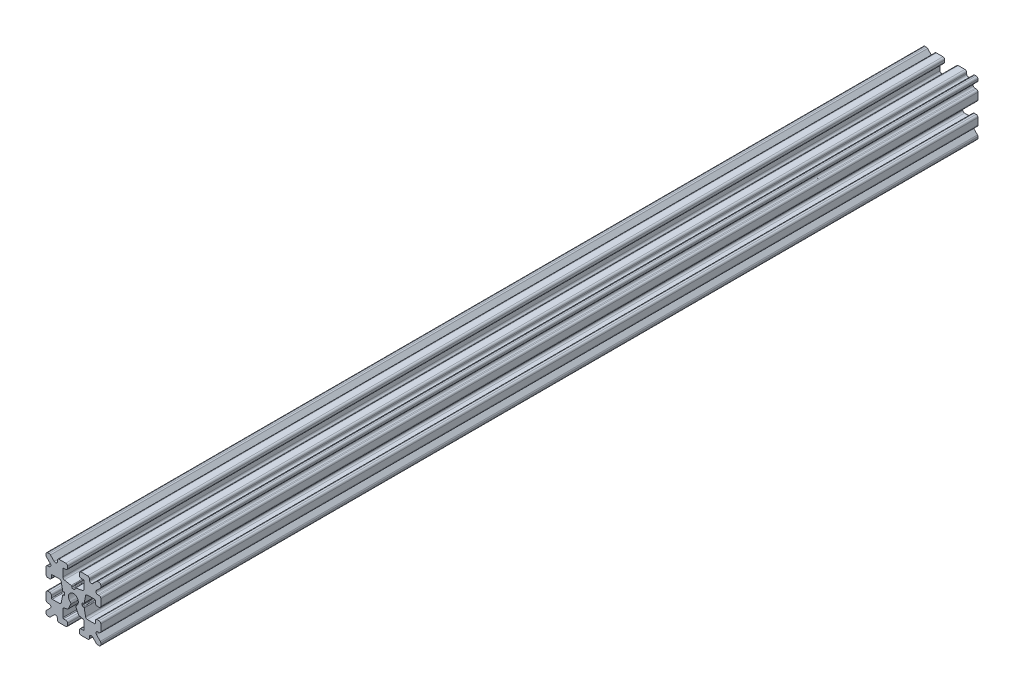
SolidWorks part; units mm, degrees
ref_plane "Front Plane" through (0, 0, 0) normal (0, 0, 1) x (1, 0, 0)
ref_plane "Top Plane" through (0, 0, 0) normal (0, 1, 0) x (1, 0, 0)
ref_plane "Right Plane" through (0, 0, 0) normal (1, 0, 0) x (0, 0, -1)
sketch "Sketch1" plane through (0, 0, 0) normal (0, 0, 1) x (1, 0, 0)
  line L1 (-7.5, -7.5) -> (7.5, -7.5)
  line L2 (-7.5, -7.5) -> (-7.5, 7.5)
  line L3 (-7.5, 7.5) -> (7.5, 7.5)
  line L4 (7.5, -7.5) -> (7.5, 7.5)
  line L5 (-7.5, -7.5) -> (7.5, 7.5) construction
  line L6 (-7.5, 7.5) -> (7.5, -7.5) construction
  circle A0 centre (0, 0) radius 1.35
  point P0 (0, 0)
  dimension "D2" = 2.7
  dimension "D1" = 15
extrude "Boss-Extrude1" add sketch "Sketch1" along normal mid plane 240
fillet "Fillet1" radius 0.5 4 edges at (7.5, -7.5, 0) (-7.5, -7.5, 0) (7.5, 7.5, 0) (-7.5, 7.5, 0)
sketch "Sketch2" plane through (0, 0, 120) normal (0, 0, 1) x (1, 0, 0)
  line L0 (-7.5, 7) -> (-7.5, -7) construction
  line L1 (-7.5, 1.6) -> (-6, 1.6)
  line L2 (-7.5, 1.6) -> (-7.5, -1.6)
  line L3 (-7.5, -1.6) -> (-6, -1.6)
  line L4 (-6, 1.6) -> (-6, 2.9)
  line L5 (0, 0) -> (-12.1036, 0) construction
  line L6 (-6, -2.9) -> (-3.4, -2.9)
  line L7 (0, 0) -> (-7, 7) construction
  line L8 (-6, 2.9) -> (-3.4, 2.9)
  line L9 (-3.4, -2.9) -> (-3.4, 2.9)
  line L10 (55, 0) -> (-55, 0) construction
  line L11 (-6, -2.9) -> (-6, -1.6)
  line L12 (2.9, 6) -> (1.6, 6)
  line L13 (2.9, 3.4) -> (-2.9, 3.4)
  line L14 (-2.9, 6) -> (-2.9, 3.4)
  line L15 (2.9, 6) -> (2.9, 3.4)
  line L16 (-1.6, 6) -> (-2.9, 6)
  line L17 (1.6, 7.5) -> (1.6, 6)
  line L18 (-1.6, 7.5) -> (1.6, 7.5)
  line L19 (-1.6, 7.5) -> (-1.6, 6)
  line L20 (-1.6, -7.5) -> (-1.6, -6)
  line L21 (-1.6, -7.5) -> (1.6, -7.5)
  line L22 (1.6, -7.5) -> (1.6, -6)
  line L23 (-1.6, -6) -> (-2.9, -6)
  line L24 (2.9, -6) -> (2.9, -3.4)
  line L25 (-2.9, -6) -> (-2.9, -3.4)
  line L26 (2.9, -3.4) -> (-2.9, -3.4)
  line L27 (2.9, -6) -> (1.6, -6)
  line L28 (6, -2.9) -> (6, -1.6)
  line L29 (3.4, -2.9) -> (3.4, 2.9)
  line L30 (6, 2.9) -> (3.4, 2.9)
  line L31 (6, -2.9) -> (3.4, -2.9)
  line L32 (6, 1.6) -> (6, 2.9)
  line L33 (7.5, -1.6) -> (6, -1.6)
  line L34 (7.5, 1.6) -> (7.5, -1.6)
  line L35 (7.5, 1.6) -> (6, 1.6)
  dimension "D1" = 3.2
  dimension "D2" = 5.8
  dimension "D3" = 1.5
  dimension "D4" = 2.6
extrude "Cut-Extrude1" cut sketch "Sketch2" against normal through all
sketch "Sketch4" plane through (0, 0, 120) normal (0, 0, 1) x (1, 0, 0)
  line L0 (-3.4, 2.9) -> (-2.85, 0)
  line L1 (55, 0) -> (-55, 0) construction
  line L2 (-2.85, 0) -> (-3.4, -2.9)
  line L3 (-3.4, -2.9) -> (-3.4, 2.9) construction
  line L4 (-3.4, 2.9) -> (-3.4, -2.9)
  line L5 (-2.9, 3.4) -> (0, 2.85)
  line L6 (0, 2.85) -> (2.9, 3.4)
  line L7 (2.9, 3.4) -> (-2.9, 3.4)
  line L8 (3.4, 2.9) -> (2.85, 0)
  line L9 (2.85, 0) -> (3.4, -2.9)
  line L10 (3.4, -2.9) -> (3.4, 2.9)
  line L11 (-2.9, -3.4) -> (0, -2.85)
  line L12 (0, -2.85) -> (2.9, -3.4)
  line L13 (2.9, -3.4) -> (-2.9, -3.4)
  circle A2 centre (0, 0) radius 2.85
  circle A3 centre (0, 0) radius 2.85 construction
  dimension "D1" = 1.5
extrude "Cut-Extrude3" cut sketch "Sketch4" against normal through all
fillet "Fillet3" radius 0.5 16 edges at (-6, -1.6, 0) (-7.5, -1.6, 0) (-6, 1.6, 0) (-7.5, 1.6, 0) (-1.6, -7.5, 0) (-1.6, -6, 0) (1.6, -7.5, 0) (1.6, -6, 0) (6, -1.6, 0) (7.5, -1.6, 0) (7.5, 1.6, 0) (6, 1.6, 0) (1.6, 7.5, 0) (1.6, 6, 0) (-1.6, 7.5, 0) (-1.6, 6, 0)
fillet "Fillet4" radius 0.5 8 edges at (-3.4, 2.9, 0) (-3.4, -2.9, 0) (2.9, -3.4, 0) (-2.9, -3.4, 0) (3.4, -2.9, 0) (3.4, 2.9, 0) (-2.9, 3.4, 0) (2.9, 3.4, 0)
fillet "Fillet5" radius 3 4 edges at (0, -2.85, 0) (2.85, 0, 0) (-2.85, 0, 0) (0, 2.85, 0)
fillet "Fillet6" radius 0.2 8 edges at (-2.9, -6, 0) (2.9, -6, 0) (6, -2.9, 0) (6, 2.9, 0) (2.9, 6, 0) (-2.9, 6, 0) (-6, -2.9, 0) (-6, 2.9, 0)
sketch "Sketch5" plane through (0, 0, 120) normal (0, 0, 1) x (1, 0, 0)
  line L0 (0, 0) -> (-7, 7) construction
  line L1 (-7.5, 6.4393) -> (-5.4607, 4.4)
  line L2 (-6.4393, 7.5) -> (-4.4, 5.4607)
  line L3 (-7.5, 4.4) -> (-5.4607, 4.4)
  line L4 (-3.8141, 2.9) -> (-5.8, 2.9) construction
  line L5 (0, 0) -> (-12.1819, 0) construction
  line L6 (-4.4, 7.5) -> (-4.4, 5.4607)
  line L7 (-2.9, 5.8) -> (-2.9, 3.8141) construction
  line L8 (-7.5, 6.4393) -> (-7.5, 4.4)
  line L9 (-7.5, 7) -> (-7.5, 2.1) construction
  line L10 (2.1, -7.5) -> (7, -7.5) construction
  line L11 (7.5, -7) -> (7.5, -2.1) construction
  line L12 (7, 7.5) -> (2.1, 7.5) construction
  line L13 (-2.1, 7.5) -> (-7, 7.5) construction
  line L14 (-4.4, 7.5) -> (-6.4393, 7.5)
  line L16 (55, 0) -> (-55, 0) construction
  line L17 (0, 0) -> (0, 10.993) construction
  line L18 (0, -54.6431) -> (0, 54.6431) construction
  line L20 (4.4, 7.5) -> (6.4393, 7.5)
  line L22 (7.5, 6.4393) -> (7.5, 4.4)
  line L23 (4.4, 7.5) -> (4.4, 5.4607)
  line L24 (7.5, 4.4) -> (5.4607, 4.4)
  line L25 (6.4393, 7.5) -> (4.4, 5.4607)
  line L26 (7.5, 6.4393) -> (5.4607, 4.4)
  line L27 (7.5, -6.4393) -> (5.4607, -4.4)
  line L28 (6.4393, -7.5) -> (4.4, -5.4607)
  line L29 (7.5, -4.4) -> (5.4607, -4.4)
  line L30 (4.4, -7.5) -> (4.4, -5.4607)
  line L31 (7.5, -6.4393) -> (7.5, -4.4)
  line L33 (4.4, -7.5) -> (6.4393, -7.5)
  line L36 (-4.4, -7.5) -> (-6.4393, -7.5)
  line L38 (-7.5, -6.4393) -> (-7.5, -4.4)
  line L39 (-4.4, -7.5) -> (-4.4, -5.4607)
  line L40 (-7.5, -4.4) -> (-5.4607, -4.4)
  line L41 (-6.4393, -7.5) -> (-4.4, -5.4607)
  line L42 (-7.5, -6.4393) -> (-5.4607, -4.4)
  dimension "D1" = 1.5
  dimension "D2" = 1.5
  dimension "D3" = 1.5
extrude "Cut-Extrude4" cut sketch "Sketch5" against normal through all
fillet "Fillet8" radius 0.5 24 edges at (-5.4607, 4.4, 0) (-7.5, 4.4, 0) (-5.4607, -4.4, 0) (-7.5, -4.4, 0) (-4.4, -7.5, 0) (-4.4, -5.4607, 0) (4.4, -7.5, 0) (4.4, -5.4607, 0) (5.4607, -4.4, 0) (7.5, -4.4, 0) (7.5, 4.4, 0) (5.4607, 4.4, 0) (4.4, 5.4607, 0) (4.4, 7.5, 0) (-4.4, 5.4607, 0) (-4.4, 7.5, 0) (-6.4393, 7.5, 0) (-7.5, 6.4393, 0) (6.4393, 7.5, 0) (7.5, 6.4393, 0) (6.4393, -7.5, 0) (7.5, -6.4393, 0) (-6.4393, -7.5, 0) (-7.5, -6.4393, 0)
sketch "Sketch6" plane through (0, 0, 120) normal (0, 0, 1) x (1, 0, 0)
  line L0 (0, 0) -> (0, 11.013) construction
  line L1 (0.559, 2.956) -> (2.1235, 2.956) construction
  line L2 (0, -54.6431) -> (0, 54.6431) construction
  line L3 (0, 0) -> (7, 7) construction
  line L4 (8.6552, 0.4445) -> (8.6552, -0.4445)
  line L5 (2.406, 0.4445) -> (8.6552, 0.4445)
  line L8 (2.406, -0.4445) -> (2.406, 0.4445)
  line L10 (8.6552, -0.4445) -> (2.406, -0.4445)
  line L11 (-8.6552, -0.4445) -> (-2.406, -0.4445)
  line L12 (-2.406, -0.4445) -> (-2.406, 0.4445)
  line L14 (-0.4445, 8.6552) -> (-0.4445, 2.406)
  line L15 (-0.4445, 2.406) -> (0.4445, 2.406)
  line L17 (0.4445, 2.406) -> (0.4445, 8.6552)
  line L18 (0.4445, 8.6552) -> (-0.4445, 8.6552)
  line L20 (-2.406, 0.4445) -> (-8.6552, 0.4445)
  line L21 (-8.6552, 0.4445) -> (-8.6552, -0.4445)
  point P7 (0, 2.5973)
  dimension "D3" = 0.55
  dimension "D1" = 0.889
extrude "Cut-Extrude5" cut sketch "Sketch6" against normal through all
sketch "Sketch7" plane through (0, 0, 120) normal (0, 0, 1) x (1, 0, 0)
  line L0 (0, 0) -> (-2.1533, -4.6178)
  line L1 (-2.1533, -4.6178) -> (2.1533, -4.6178)
  line L2 (2.1533, -4.6178) -> (0, 0)
  line L3 (0, 0) -> (0, -8.6832) construction
  line L4 (0, -54.6431) -> (0, 54.6431) construction
  dimension "D1" = 50
extrude "Cut-Extrude6" cut sketch "Sketch7" against normal through all
fillet "Fillet9" radius 0.5 4 edges at (0.5705, -1.2235, 0) (-0.5705, -1.2235, 0) (1.4579, -3.1265, 0) (-1.4579, -3.1265, 0)
fillet "Fillet10" radius 0.2 12 edges at (-2.406, 0.4445, 0) (-2.406, -0.4445, 0) (0.4445, 2.406, 0) (-0.4445, 2.406, 0) (2.406, 0.4445, 0) (2.406, -0.4445, 0) (-2.9366, -0.4445, 0) (-2.9366, 0.4445, 0) (2.9366, -0.4445, 0) (2.9366, 0.4445, 0) (0.4445, 2.9366, 0) (-0.4445, 2.9366, 0)
sketch "Sketch10" plane through (0, 0, 120) normal (0, 0, 1) x (1, 0, 0)
  line L0 (2.7, 6) -> (2.1, 6) construction
  line L1 (-2.75, 6) -> (2.75, 6)
  line L2 (-2.75, 6) -> (-2.75, 3.6)
  line L3 (-2.75, 3.6) -> (2.75, 3.6)
  line L4 (2.75, 6) -> (2.75, 3.6)
  line L5 (0, 0) -> (0, 8.8277) construction
  line L6 (-3.2398, 3.994) -> (-2.2083, 2.8606) construction
  line L7 (-3.878, 3.2131) -> (-3.2018, 2.4701) construction
  line L8 (-2.406, -0.2445) -> (-2.406, 0.2445) construction
  line L9 (-2.1, 7.5) -> (-3.9, 7.5) construction
  line L10 (-1.5, 7.5) -> (1.5, 7.5)
  line L11 (-1.5, 7.5) -> (-1.5, 3.5)
  line L12 (-1.5, 3.5) -> (1.5, 3.5)
  line L13 (1.5, 7.5) -> (1.5, 3.5)
  arc A1 (-3.3228, 2.4932) -> (-3.8141, 2.9) centre (-3.8141, 2.4) ccw construction
  arc A2 (-2.9, 3.8141) -> (-2.4932, 3.3228) centre (-2.4, 3.8141) ccw construction
  arc A3 (0.88, -1.0238) -> (-0.88, -1.0238) centre (0, 0) ccw construction
  point P19 (-1.35, 0)
  point P20 (-2.406, 0)
  dimension "D1" = 2.4
  dimension "D2" = 5.5
  dimension "D3" = 0.9976
  dimension "D4" = 3
  dimension "D5" = 4
sketch "Sketch11" plane through (0, 0, 120) normal (0, 0, 1) x (1, 0, 0)
  line L0 (-7.5, 7) -> (-7.5, 6.6464) construction
  line L1 (-7.5, 7.5) -> (7.5, 7.5) construction
  line L2 (-7.5, 7.5) -> (-7.5, -7.5) construction
  line L3 (-7.5, -7.5) -> (7.5, -7.5) construction
  line L4 (7.5, 7.5) -> (7.5, -7.5) construction
  line L5 (-7, -7.5) -> (-6.6464, -7.5) construction
  line L6 (7.5, 6.6464) -> (7.5, 7) construction
  line L7 (-2.1, 7.5) -> (-3.9, 7.5) construction
  point P0 (0, 7.5)
  point P1 (0, -7.5)
  point P2 (7.5, 0)
  point P3 (-7.5, 0)
sketch "Sketch12" plane through (0, 0, -120) normal (0, 0, -1) x (-1, 0, 0)
  line L1 (-7.5, -7.5) -> (7.5, -7.5) construction
  line L2 (-7.5, -7.5) -> (-7.5, 7.5) construction
  line L3 (-7.5, 7.5) -> (7.5, 7.5) construction
  line L4 (7.5, -7.5) -> (7.5, 7.5) construction
  point P4 (-7.5, 0)
  point P9 (0, -7.5)
  point P10 (7.5, 0)
  point P11 (0, 7.5)
sketch "Sketch13" plane through (0, -7.5, 0) normal (0, -1, 0) x (1, 0, 0)
  line L0 (0, 120) -> (0, -120) construction
  line L1 (-7.5, -120) -> (-7.5, 120) construction
  line L2 (7.5, 120) -> (7.5, -120) construction
sketch "Sketch14" plane through (-7.5, 0, 0) normal (-1, 0, 0) x (0, 0, 1)
  line L0 (120, 0) -> (-120, 0) construction
sketch "Sketch15" plane through (0, 7.5, 0) normal (0, 1, 0) x (1, 0, 0)
  line L0 (0, -120) -> (0, 120) construction
  line L1 (-7.5, -120) -> (7.5, -120) construction
  line L2 (-7.5, -120) -> (-7.5, 120) construction
  line L3 (7.5, 120) -> (7.5, -120) construction
sketch "Sketch16" plane through (7.5, 0, 0) normal (1, 0, 0) x (0, 0, -1)
  line L0 (-120, 0) -> (120, 0) construction
